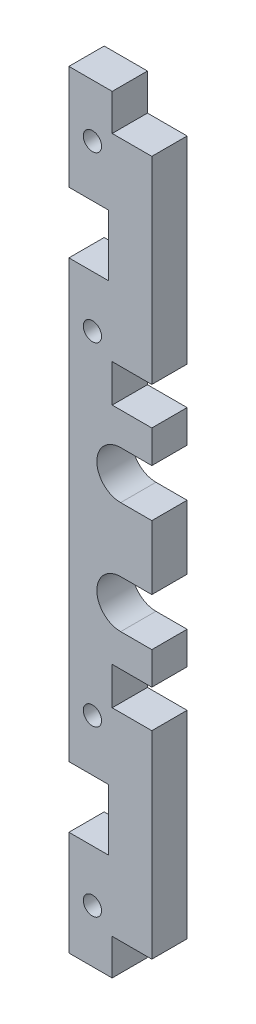
SolidWorks part; units mm, degrees
ref_plane "Płaszczyzna przednia" through (0, 0, 0) normal (0, 0, 1) x (1, 0, 0)
ref_plane "Płaszczyzna górna" through (0, 0, 0) normal (0, 1, 0) x (1, 0, 0)
ref_plane "Płaszczyzna prawa" through (0, 0, 0) normal (1, 0, 0) x (0, 0, -1)
sketch "Szkic1" plane through (0, 0, 0) normal (0, 0, 1) x (1, 0, 0)
  line L0 (-79.4505, -66.58) -> (-79.4505, 70)
  line L1 (-79.4505, -66.58) -> (-65.3505, -66.58)
  line L2 (-79.4505, 70) -> (-65.3505, 70)
  line L3 (-65.3505, -66.58) -> (-65.3505, 70)
  line L4 (-71.8889, -66.58) -> (-65.3389, -66.58) construction
  line L9 (-79.4505, 6) -> (-79.4505, 0) construction
  dimension "D1" = 0
  dimension "D2" = 0
  dimension "D3" = 14.1
extrude "Dodanie-wyciągnięcie1" add sketch "Szkic1" against normal blind 6
other "Przenieś ścianę1" face at (-72.4005, -66.58, -3) parameters "D1"=6
sketch "Szkic2" plane through (0, 0, 0) normal (0, 0, 1) x (1, 0, 0)
  line L0 (-65.3505, 70) -> (-79.4505, 70) construction
  line L1 (-71.8889, 70) -> (-65.3389, 70)
  line L2 (-71.8889, 70) -> (-71.8889, 64)
  line L3 (-71.8889, 64) -> (-65.3389, 64)
  line L4 (-65.3389, 70) -> (-65.3389, 64)
  line L5 (-65.3389, 0) -> (-65.3389, 6) construction
  line L10 (-65.3389, 30) -> (-71.8889, 30) construction
  line L11 (-71.8889, 30) -> (-71.8889, 24) construction
  line L12 (-79.4505, -60.58) -> (-65.3505, -60.58) construction
  line L13 (-71.9005, -60.58) -> (-65.3505, -60.58)
  line L14 (-71.9005, -60.58) -> (-71.9005, -54.6371)
  line L15 (-71.9005, -54.6371) -> (-65.3505, -54.6371)
  line L16 (-65.3505, -60.58) -> (-65.3505, -54.6371)
  line L17 (-72.1005, -60.78) -> (-72.1005, -54.4371)
  line L22 (-72.1005, -54.4371) -> (-65.1505, -54.4371)
  line L23 (-65.1505, -60.78) -> (-65.1505, -54.4371)
  line L24 (-72.1005, -60.78) -> (-65.1505, -60.78)
  line L29 (-72.0889, 70.2) -> (-72.0889, 63.8)
  line L30 (-72.0889, 63.8) -> (-65.1389, 63.8)
  line L31 (-65.1389, 70.2) -> (-65.1389, 63.8)
  line L32 (-72.0889, 70.2) -> (-65.1389, 70.2)
  line L40 (-65.3505, -60.58) -> (-65.3505, 70) construction
  line L41 (-71.8889, 24) -> (-65.3389, 24) construction
  line L42 (-65.3389, 24) -> (-65.3389, 30) construction
  line L46 (-65.3389, 30) -> (-71.8889, 30)
  line L47 (-71.8889, 30) -> (-71.8889, 24)
  line L48 (-71.8889, 24) -> (-65.3389, 24)
  line L49 (-65.3389, 24) -> (-65.3389, 30)
  line L50 (-71.8889, -20.58) -> (-65.3389, -20.58)
  line L51 (-71.8889, -14.58) -> (-71.8889, -20.58)
  line L52 (-65.3389, -14.58) -> (-71.8889, -14.58)
  line L53 (-65.3389, -20.58) -> (-65.3389, -14.58)
  line L54 (-72.0889, 30.2) -> (-72.0889, 23.8)
  line L55 (-72.0889, 23.8) -> (-65.1389, 23.8)
  line L56 (-65.1389, 23.8) -> (-65.1389, 30.2)
  line L57 (-65.1389, 30.2) -> (-72.0889, 30.2)
  line L58 (-72.0889, -14.38) -> (-72.0889, -20.78)
  line L59 (-72.0889, -20.78) -> (-65.1389, -20.78)
  line L60 (-65.1389, -20.78) -> (-65.1389, -14.38)
  line L61 (-65.1389, -14.38) -> (-72.0889, -14.38)
  line L69 (-79.4505, 52.2) -> (-72.7005, 52.2)
  line L74 (-72.7005, 52.2) -> (-72.7005, 41.8)
  line L75 (-72.7005, 41.8) -> (-79.4505, 41.8)
  line L77 (-79.4505, -32.3903) -> (-72.7005, -32.3903)
  line L80 (-72.7005, -32.3903) -> (-72.7005, -42.7903)
  line L81 (-72.7005, -42.7903) -> (-79.4505, -42.7903)
  line L82 (-79.4505, -32.3903) -> (-79.4505, -42.7903)
  line L83 (-79.4505, 41.8) -> (-79.4505, 52.2)
  dimension "D1" = 0
  dimension "D2" = 6.55
  dimension "D3" = 10.4
  dimension "D4" = 6.75
  dimension "D5" = 6
  dimension "D6" = 17.7897
  dimension "D7" = 6.55
  dimension "D8" = 5.9429
  dimension "D9" = 6
  dimension "D10" = 0
  dimension "D13" = 6.55
  dimension "D14" = 11.8103
  dimension "D11" = 0.2
  dimension "D12" = 0.2
sketch "Szkic3" plane through (0, 0, 0) normal (0, 0, 1) x (1, 0, 0)
  line L0 (-72.0889, 70.2) -> (-72.0889, 63.8) construction
  line L1 (-72.0889, 63.8) -> (-65.1389, 63.8) construction
  line L2 (-65.1389, 70.2) -> (-65.1389, 63.8) construction
  line L3 (-72.0889, 70.2) -> (-65.1389, 70.2) construction
  line L8 (-79.4505, -32.3903) -> (-72.7005, -32.3903) construction
  line L9 (-79.4505, -32.3903) -> (-72.7005, -32.3903)
  line L10 (-79.4505, -32.3903) -> (-79.4505, -42.7903) construction
  line L11 (-72.7005, -42.7903) -> (-79.4505, -42.7903) construction
  line L12 (-65.1389, 30.2) -> (-72.0889, 30.2) construction
  line L13 (-72.0889, 30.2) -> (-72.0889, 23.8) construction
  line L14 (-72.0889, 23.8) -> (-65.1389, 23.8) construction
  line L15 (-65.1389, 23.8) -> (-65.1389, 30.2) construction
  line L16 (-72.1005, -60.78) -> (-72.1005, -54.4371) construction
  line L17 (-72.1005, -54.4371) -> (-65.1505, -54.4371) construction
  line L18 (-65.1505, -60.78) -> (-65.1505, -54.4371) construction
  line L19 (-72.1005, -60.78) -> (-65.1505, -60.78) construction
  line L20 (-65.1389, -14.38) -> (-72.0889, -14.38) construction
  line L21 (-72.0889, -14.38) -> (-72.0889, -20.78) construction
  line L22 (-72.0889, -20.78) -> (-65.1389, -20.78) construction
  line L23 (-65.1389, -20.78) -> (-65.1389, -14.38) construction
  line L24 (-72.0889, 70.2) -> (-72.0889, 63.8)
  line L25 (-72.0889, 63.8) -> (-65.1389, 63.8)
  line L26 (-65.1389, 70.2) -> (-65.1389, 63.8)
  line L27 (-72.0889, 70.2) -> (-65.1389, 70.2)
  line L28 (-65.1389, 30.2) -> (-72.0889, 30.2)
  line L29 (-72.0889, 30.2) -> (-72.0889, 23.8)
  line L30 (-72.0889, 23.8) -> (-65.1389, 23.8)
  line L31 (-65.1389, 23.8) -> (-65.1389, 30.2)
  line L32 (-72.1005, -60.78) -> (-72.1005, -54.4371)
  line L33 (-72.1005, -54.4371) -> (-65.1505, -54.4371)
  line L34 (-65.1505, -60.78) -> (-65.1505, -54.4371)
  line L35 (-72.1005, -60.78) -> (-65.1505, -60.78)
  line L36 (-65.1389, -14.38) -> (-72.0889, -14.38)
  line L37 (-72.0889, -14.38) -> (-72.0889, -20.78)
  line L38 (-72.0889, -20.78) -> (-65.1389, -20.78)
  line L39 (-65.1389, -20.78) -> (-65.1389, -14.38)
  line L44 (-72.7005, -32.3903) -> (-72.7005, -42.7903) construction
  line L45 (-79.4505, 41.8) -> (-79.4505, 52.2) construction
  line L46 (-79.4505, 52.2) -> (-72.7005, 52.2) construction
  line L47 (-72.7005, 52.2) -> (-72.7005, 41.8) construction
  line L48 (-72.7005, 41.8) -> (-79.4505, 41.8) construction
  line L49 (-79.4505, -32.3903) -> (-79.4505, -42.7903)
  line L50 (-72.7005, -42.7903) -> (-79.4505, -42.7903)
  line L51 (-72.7005, -32.3903) -> (-72.7005, -42.7903)
  line L52 (-79.4505, 41.8) -> (-79.4505, 52.2)
  line L53 (-79.4505, 52.2) -> (-72.7005, 52.2)
  line L54 (-72.7005, 52.2) -> (-72.7005, 41.8)
  line L55 (-72.7005, 41.8) -> (-79.4505, 41.8)
extrude "Wytnij-wyciągnięcie1" cut sketch "Szkic3" against normal through all
sketch "Szkic4" plane through (0, 0, 0) normal (0, 0, 1) x (1, 0, 0)
  line L0 (-79.4505, 70) -> (-79.4505, 52.2) construction
  line L1 (-72.0889, 70) -> (-79.4505, 70) construction
  line L2 (-79.4505, -60.58) -> (-72.1005, -60.58) construction
  line L3 (-79.4505, -42.7903) -> (-79.4505, -60.58) construction
  circle A0 centre (-75.4505, 61) radius 1.55
  circle A1 centre (-75.4505, -51.58) radius 1.55
  circle A2 centre (-75.4505, 33) radius 1.55
  circle A3 centre (-75.4505, -23.58) radius 1.55
  dimension "D1" = 4
  dimension "D2" = 4
  dimension "D3" = 9
  dimension "D4" = 9
  dimension "D5" = 3.1
  dimension "D6" = 3.1
  dimension "D7" = 3.1
  dimension "D8" = 0
  dimension "D9" = 28
  dimension "D10" = 3.1
  dimension "D11" = 4
  dimension "D12" = 28
extrude "Wytnij-wyciągnięcie2" cut sketch "Szkic4" against normal through all
sketch "Szkic5" plane through (0, 0, -6) normal (0, 0, -1) x (-1, 0, 0)
  line L4 (65.3505, -0.7452) -> (65.3505, -8.8452)
  line L8 (65.3505, -8.8452) -> (70.6505, -8.8452)
  line L9 (70.6505, -0.7452) -> (65.3505, -0.7452)
  line L10 (65.3505, 10.1548) -> (70.6505, 10.1548)
  line L11 (70.6505, 18.2548) -> (65.3505, 18.2548)
  line L12 (65.3505, 18.2548) -> (65.3505, 10.1548)
  line L13 (65.3505, -14.38) -> (65.3505, 23.8) construction
  arc A4 (70.6505, -8.8452) -> (70.6505, -0.7452) centre (70.6505, -4.7952) ccw
  arc A5 (70.6505, 10.1548) -> (70.6505, 18.2548) centre (70.6505, 14.2048) ccw
  point P1 (70.6505, -6.3452)
  point P2 (70.6505, -3.2452)
  point P4 (70.6505, 12.6548)
  point P5 (70.6505, 15.7548)
  point P6 (61.1505, 12.6548)
  point P7 (61.1505, 15.7548)
  point P8 (61.1505, -6.3452)
  point P9 (61.1505, -3.2452)
  point P10 (61.1505, -8.8452)
  point P14 (61.1505, -0.7452)
  point P15 (61.1505, 10.1548)
  point P19 (61.1505, 18.2548)
extrude "Wytnij-wyciągnięcie3" cut sketch "Szkic5" against normal blind 10
equation "\"tolerancja_wpusy\"=0.2"
equation "\"dlugosc_wpustu_duzy\"=20"
equation "\"srednica_otworu_M3\"=3.1"
equation "\"szerokosc_nogi_T\"=3.1"
equation "\"dlugosc_T_30\"=11"
equation "\"grubosc_na_nakretke_kwadrat\"=2"
equation "\"szerokosc_na_nakretke_kwadrat\"=5.85"
equation "\"wyokosc_nadstawki_T\"=0.5"
equation "\"dlugosc_T_20_6\"=14"
equation "\"D5@Szkic4\"=\"srednica_otworu_M3\""
equation "\"D6@Szkic4\"=\"srednica_otworu_M3\""
equation "\"D7@Szkic4\"=\"srednica_otworu_M3\""
equation "\"D10@Szkic4\"=\"srednica_otworu_M3\""
